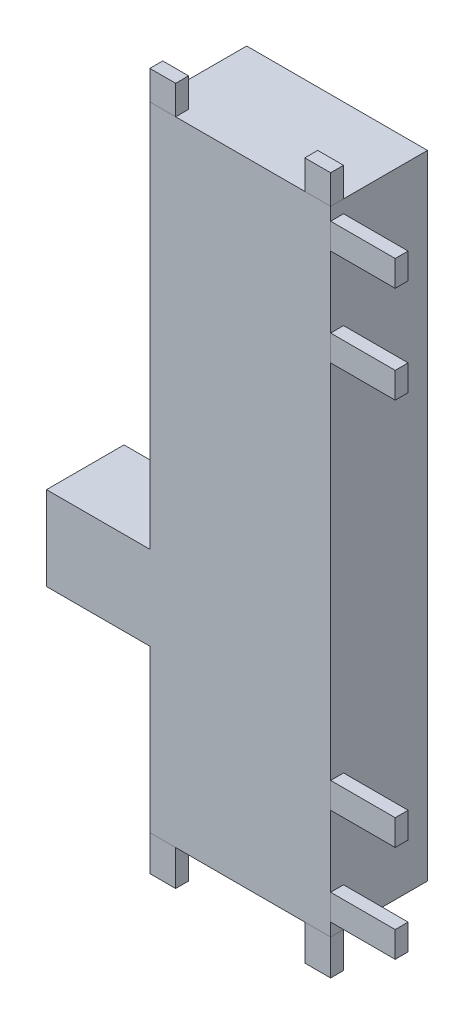
SolidWorks part; units mm, degrees
ref_plane "Front Plane" through (0, 0, 0) normal (0, 0, 1) x (1, 0, 0)
ref_plane "Top Plane" through (0, 0, 0) normal (0, 1, 0) x (1, 0, 0)
ref_plane "Right Plane" through (0, 0, 0) normal (1, 0, 0) x (0, 0, -1)
sketch "Sketch1" plane through (0, 0, 0) normal (0, 0, 1) x (1, 0, 0)
  line L1 (-1.4, 4.9) -> (1.4, 4.9)
  line L2 (-1.4, 4.9) -> (-1.4, -4.9)
  line L3 (-1.4, -4.9) -> (1.4, -4.9)
  line L4 (1.4, 4.9) -> (1.4, -4.9)
  line L5 (-1.4, 4.9) -> (1.4, -4.9) construction
  line L6 (-1.4, -4.9) -> (1.4, 4.9) construction
  point P0 (0, 0)
  dimension "D1" = 2.8
  dimension "D2" = 9.8
extrude "Boss-Extrude1" add sketch "Sketch1" along normal blind 1.5
sketch "Sketch2" plane through (0, 0, 1.5) normal (0, 0, 1) x (1, 0, 0)
  line L0 (1.4, -4.9) -> (1.4, 4.9) construction
  line L1 (1.4, -4.7) -> (2.4, -4.7)
  line L2 (1.4, -4.7) -> (1.4, -4.3)
  line L3 (1.4, -4.3) -> (2.4, -4.3)
  line L4 (2.4, -4.7) -> (2.4, -4.3)
  line L5 (-1.4, 4.9) -> (-1.4, -4.9) construction
  line L6 (1.4, -3.2) -> (2.4, -3.2)
  line L7 (1.4, -3.2) -> (1.4, -2.8)
  line L8 (1.4, -2.8) -> (2.4, -2.8)
  line L9 (2.4, -3.2) -> (2.4, -2.8)
  line L10 (1.4, 2.8) -> (2.4, 2.8)
  line L11 (1.4, 2.8) -> (1.4, 3.2)
  line L12 (1.4, 3.2) -> (2.4, 3.2)
  line L13 (2.4, 2.8) -> (2.4, 3.2)
  line L14 (1.4, 4.3) -> (2.4, 4.3)
  line L15 (1.4, 4.3) -> (1.4, 4.7)
  line L16 (1.4, 4.7) -> (2.4, 4.7)
  line L17 (2.4, 4.3) -> (2.4, 4.7)
  line L18 (-1.4, -1.1) -> (-3, -1.1)
  line L19 (-1.4, -1.1) -> (-1.4, -2.4)
  line L20 (-1.4, -2.4) -> (-3, -2.4)
  line L21 (-3, -1.1) -> (-3, -2.4)
  line L22 (1.4, 4.9) -> (-1.4, 4.9) construction
  line L23 (-1.4, -4.9) -> (-1, -4.9)
  line L24 (-1.4, -4.9) -> (-1.4, -5.45)
  line L25 (-1.4, -5.45) -> (-1, -5.45)
  line L26 (-1, -4.9) -> (-1, -5.45)
  line L27 (1.4, -4.9) -> (1, -4.9)
  line L28 (1.4, -4.9) -> (1.4, -5.45)
  line L29 (1.4, -5.45) -> (1, -5.45)
  line L30 (1, -4.9) -> (1, -5.45)
  line L31 (-1.4, 4.9) -> (-1, 4.9)
  line L32 (-1.4, 4.9) -> (-1.4, 5.35)
  line L33 (-1.4, 5.35) -> (-1, 5.35)
  line L34 (-1, 4.9) -> (-1, 5.35)
  line L35 (1.4, 4.9) -> (1, 4.9)
  line L36 (1.4, 4.9) -> (1.4, 5.35)
  line L37 (1.4, 5.35) -> (1, 5.35)
  line L38 (1, 4.9) -> (1, 5.35)
  point P24 (2.4, 3)
  point P26 (2.4, -3)
  point P27 (2.4, -4.5)
  point P28 (2.4, 4.5)
  dimension "D1" = 1
  dimension "D2" = 0.4
  dimension "D3" = 3
  dimension "D4" = 3
  dimension "D5" = 1.5
  dimension "D6" = 1.5
  dimension "D7" = 1.3
  dimension "D8" = 1.6
  dimension "D9" = 0.4
  dimension "D10" = 0.55
  dimension "D11" = 10.8
  dimension "D12" = 0.55
  dimension "D13" = 10.8
  dimension "D14" = 0.4
  dimension "D15" = 0.4
  dimension "D16" = 0.4
  dimension "D17" = 6
extrude "Boss-Extrude2" add sketch "Sketch2" against normal blind 0.2 separate body
sketch "Sketch3" plane through (0, 0, 0) normal (0, 0, -1) x (-1, 0, 0)
  line L0 (0, -2.5) -> (0, 2.5) construction
  line L1 (1.4, -4.9) -> (-1.4, -4.9) construction
  circle A0 centre (0, -2.5) radius 0.4
  circle A1 centre (0, 2.5) radius 0.4
  point P4 (0, 0)
  dimension "D2" = 0.8
  dimension "D3" = 0.8
  dimension "D1" = 5
extrude "Boss-Extrude3" add sketch "Sketch3" along normal blind 0.5 contours A0
sketch "Sketch4" plane through (0, 0, 0) normal (1, 0, 0) x (0, 0, -1)
  line L0 (-34.5756, -156.9416) -> (-395.2423, -156.9416) construction
  line L1 (-1.2349, -2.8691) -> (-0.7445, -2.8691)
  line L2 (-0.7445, -2.8691) -> (-0.7445, 1.3094)
  line L3 (-0.7445, 1.3094) -> (-0.1907, 1.3094)
  line L4 (-0.1907, 1.3094) -> (-0.1907, 2.6156)
  line L5 (-0.1907, 2.6156) -> (-1.2349, 2.6156)
  line L6 (-1.2349, -2.8691) -> (-1.5, -2.8691)
  line L7 (-1.5, -3.2) -> (-1.5, -2.8) construction
  line L8 (-1.5, -2.8691) -> (-1.5, 2.6156)
  line L9 (-1.5, -4.9) -> (-1.5, 4.9) construction
  line L10 (-1.5, 2.6156) -> (-1.2349, 2.6156)
extrude "Cut-Extrude1" cut sketch "Sketch4" against normal mid plane 2 contours L2 L3 L4 L5 L10 L8 L6 L1
sketch "Sketch5" plane through (0, 0, 1.3) normal (0, 0, -1) x (-1, 0, 0)
  line L4 (1.4, -1.1) -> (1.4, -2.4)
  line L5 (1.4, -2.4) -> (3, -2.4)
  line L6 (3, -2.4) -> (3, -1.1)
  line L7 (3, -1.1) -> (1.4, -1.1)
  line L8 (1.4, -1.1) -> (1.4, -2.4)
  line L9 (1.4, -2.4) -> (3, -2.4)
  line L10 (3, -2.4) -> (3, -1.1)
  line L11 (3, -1.1) -> (1.4, -1.1)
  dimension "D1" = 0
extrude "Boss-Extrude4" add sketch "Sketch5" along normal blind 1
sketch "Sketch6" plane through (0, 0, 1.5) normal (0, 0, 1) x (1, 0, 0)
  line L0 (-1, 2.6156) -> (1, 2.6156) construction
  line L1 (1, -2.8691) -> (1, 2.6156) construction
  line L2 (-1, -2.8691) -> (1, -2.8691) construction
  line L3 (-1, -2.8691) -> (-1, 2.6156) construction
  line L4 (-1, 2.6156) -> (1, 2.6156)
  line L5 (1, -2.8691) -> (1, 2.6156)
  line L6 (-1, -2.8691) -> (1, -2.8691)
  line L7 (-1, -2.8691) -> (-1, 2.6156)
extrude "Boss-Extrude5" add sketch "Sketch6" against normal blind 0.1
